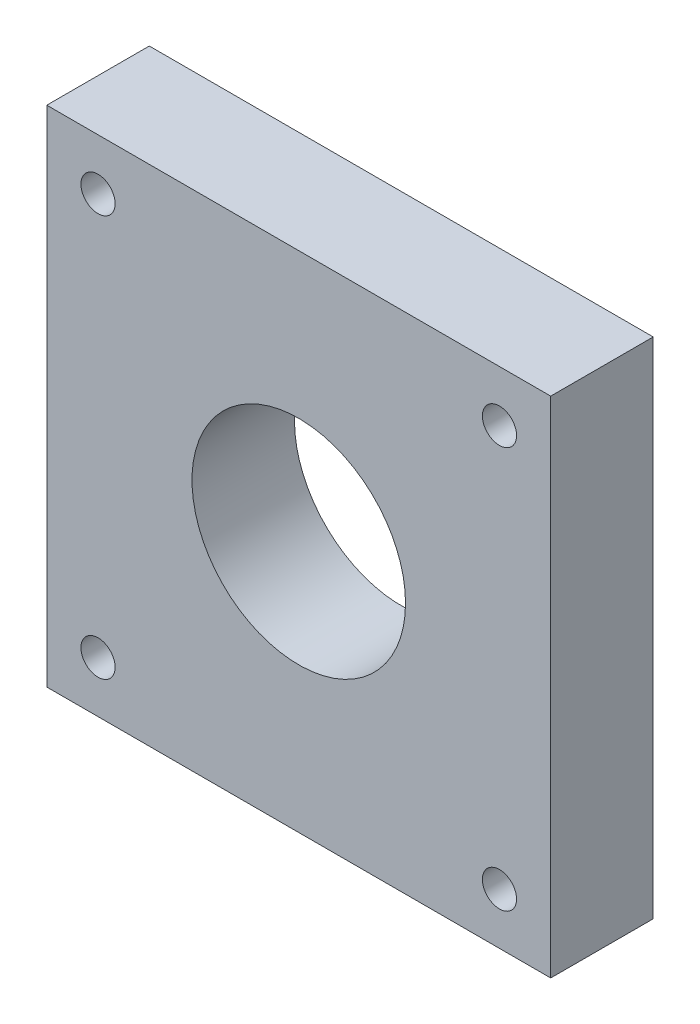
SolidWorks part; units mm, degrees
material "Beech"
ref_plane "Front Plane" through (0, 0, 0) normal (0, 0, 1) x (1, 0, 0)
ref_plane "Top Plane" through (0, 0, 0) normal (0, 1, 0) x (1, 0, 0)
ref_plane "Right Plane" through (0, 0, 0) normal (1, 0, 0) x (0, 0, -1)
sketch "Sketch1" plane through (0, 0, 0) normal (0, 0, 1) x (1, 0, 0)
  line L1 (-29.5, -29.5) -> (29.5, -29.5)
  line L2 (-29.5, -29.5) -> (-29.5, 29.5)
  line L3 (-29.5, 29.5) -> (29.5, 29.5)
  line L4 (29.5, -29.5) -> (29.5, 29.5)
  line L5 (-29.5, -29.5) -> (29.5, 29.5) construction
  line L6 (-29.5, 29.5) -> (29.5, -29.5) construction
  point P0 (0, 0)
  dimension "D1" = 59
  dimension "D2" = 59
extrude "Boss-Extrude1" add sketch "Sketch1" along normal blind 12
sketch "Sketch2" plane through (0, 0, 12) normal (0, 0, 1) x (1, 0, 0)
  line L0 (0, 29.458) -> (0, -31.6928) construction
  line L1 (-30.8337, 0) -> (30.2369, 0) construction
  circle A0 centre (-23.5, 23.5) radius 2
  dimension "D3" = 4
  dimension "D1" = 23.5
  dimension "D2" = 23.5
extrude "Cut-Extrude1" cut sketch "Sketch2" against normal up to next
mirror "Mirror1" about plane through (0, 0, 0) normal (1, 0, 0) of "Cut-Extrude1"
mirror "Mirror2" about plane through (0, 0, 0) normal (0, 1, 0) of "Cut-Extrude1", "Mirror1"
sketch "Sketch3" plane through (0, 0, 12) normal (0, 0, 1) x (1, 0, 0)
  circle A0 centre (0, 0) radius 12.5
  dimension "D1" = 25
extrude "Cut-Extrude2" cut sketch "Sketch3" against normal up to next
